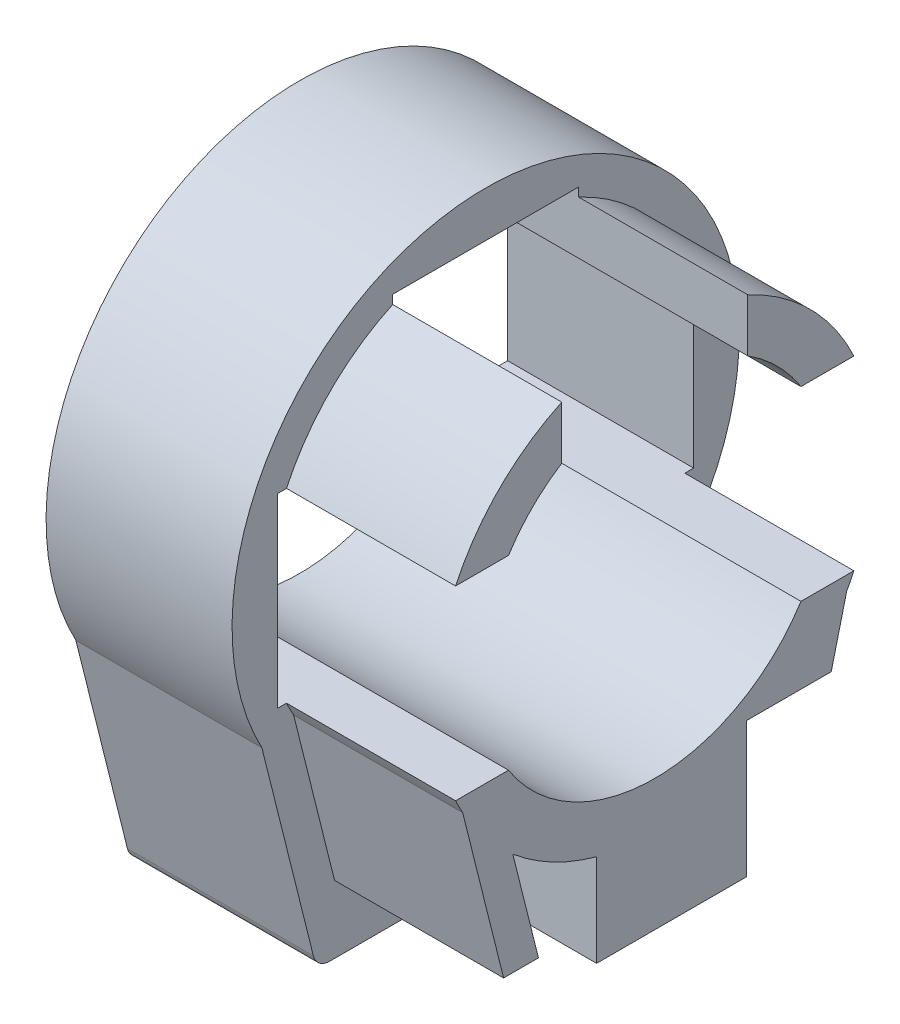
SolidWorks part; units mm, degrees
ref_plane "Alzado" through (0, 0, 0) normal (0, 0, 1) x (1, 0, 0)
ref_plane "Planta" through (0, 0, 0) normal (0, 1, 0) x (1, 0, 0)
ref_plane "Vista lateral" through (0, 0, 0) normal (1, 0, 0) x (0, 0, -1)
sketch "Croquis1" plane through (0, 0, 0) normal (1, 0, 0) x (0, 0, -1)
  line L0 (-15, 35) -> (-15, 30) construction
  line L1 (-5.7808, 0) -> (-24.2192, 0)
  line L5 (-15, 30) -> (-15, 10) construction
  line L6 (-25, 20) -> (-25, 0) construction
  line L7 (-5, 20) -> (-5, 0) construction
  line L8 (-28.2353, 12.9412) -> (-25.1894, 0.7575)
  line L9 (-1.7647, 12.9412) -> (-4.8106, 0.7575)
  circle A0 centre (-15, 20) radius 10
  arc A1 (-1.7647, 12.9412) -> (-28.2353, 12.9412) centre (-15, 20) ccw
  arc A2 (-24.2192, 0) -> (-25.1894, 0.7575) centre (-24.2192, 1) cw
  arc A3 (-5.7808, 0) -> (-4.8106, 0.7575) centre (-5.7808, 1) ccw
  dimension "D1" = 1
  dimension "D2" = 35
  dimension "D3" = 20
  dimension "D4" = 5
extrude "Saliente-Extruir1" add sketch "Croquis1" along normal blind 11
sketch "Croquis2" plane through (11, 0, 0) normal (1, 0, 0) x (0, 0, -1)
  line L9 (-23.4384, 2) -> (-6.5616, 2)
  line L10 (-6.5616, 2) -> (-3.6431, 13.6738)
  line L11 (-26.3569, 13.6738) -> (-23.4384, 2)
  line L12 (-23.4384, 2) -> (-6.5616, 2)
  line L13 (-6.5616, 2) -> (-3.6431, 13.6738)
  line L14 (-26.3569, 13.6738) -> (-23.4384, 2)
  circle A6 centre (-15, 20) radius 10 construction
  circle A7 centre (-15, 20) radius 10
  arc A9 (-3.6431, 13.6738) -> (-26.3569, 13.6738) centre (-15, 20) ccw
  arc A10 (-3.6431, 13.6738) -> (-26.3569, 13.6738) centre (-15, 20) ccw
  dimension "D1" = 2
extrude "Saliente-Extruir2" add sketch "Croquis2" along normal blind 10
sketch "Croquis3" plane through (21, 0, 0) normal (1, 0, 0) x (0, 0, -1)
  line L0 (-9.5616, 2) -> (-9.5616, 10)
  line L1 (-23.4384, 2) -> (-6.5616, 2) construction
  line L2 (-9.5616, 10) -> (-4.5616, 10)
  line L3 (-6.5616, 2) -> (-3.6431, 13.6738) construction
  line L4 (-9.5616, 2) -> (-6.5616, 2)
  line L5 (-6.5616, 2) -> (-4.5616, 10)
  line L6 (-21.7673, 2) -> (-21.7673, 4) construction
  line L7 (-23.4384, 2) -> (-18.4384, 2)
  line L8 (-23.4384, 2) -> (-23.9384, 4)
  line L9 (-21.7673, 4) -> (-21.8769, 4) construction
  line L10 (-24.4166, 14.1589) -> (-21.4982, 2.4851)
  line L11 (-23.1946, 9.2708) -> (-21.8769, 4)
  line L12 (-21.8769, 4) -> (-23.9384, 4)
  line L13 (-26.3569, 13.6738) -> (-23.4384, 2) construction
  line L14 (-18.4384, 2) -> (-18.4384, 6.9452)
  line L15 (-23.1946, 9.2708) -> (-23.3955, 10.0745)
  line L16 (-18.4384, 6.9452) -> (-18.4384, 7.463)
  circle A6 centre (-15, 20) radius 13
  arc A7 (-23.3955, 10.0745) -> (-18.4384, 7.463) centre (-15, 20) ccw
  dimension "D2" = 8
  dimension "D3" = 5
  dimension "D4" = 2
  dimension "D6" = 5
  dimension "D5" = 2
  dimension "D7" = 3
extrude "Cortar-Extruir3" cut sketch "Croquis3" against normal blind 10
sketch "Croquis8" plane through (0, 2, 0) normal (0, -1, 0) x (1, 0, 0)
  line L1 (11, 14) -> (13.2177, 14) construction
  line L2 (11, 18.4384) -> (11, 9.5616) construction
  line L4 (14.45, 14) -> (16, 14) construction
  line L5 (16, 14) -> (17.55, 14) construction
  line L7 (17.55, 14) -> (21, 14) construction
  line L8 (21, 18.4384) -> (21, 9.5616) construction
  circle A0 centre (16, 14) radius 1.55
  dimension "D2" = 3.1
extrude "Cortar-Extruir4" cut sketch "Croquis8" against normal blind 5
sketch "Croquis10" plane through (0, 0, 0) normal (-1, 0, 0) x (0, 0, 1)
  line L4 (15, 32.3) -> (20.5, 32.3)
  line L5 (2.7, 20) -> (5, 20)
  line L6 (2.7, 20) -> (2.7, 25.5)
  line L9 (2.7, 20) -> (2.7, 14.5)
  line L10 (15, 32.3) -> (9.5, 32.3)
  line L11 (2.7, 25.5) -> (6.3506, 25.5)
  line L12 (2.7, 14.5) -> (6.3506, 14.5)
  line L13 (20.5, 32.3) -> (20.5, 28.6494)
  line L14 (9.5, 32.3) -> (9.5, 28.6494)
  line L16 (27.3, 20) -> (27.3, 14.5)
  line L17 (27.3, 20) -> (27.3, 25.5)
  line L18 (27.3, 14.5) -> (23.6494, 14.5)
  line L19 (27.3, 25.5) -> (23.6494, 25.5)
  line L21 (15, 20) -> (15, 30.25) construction
  arc A1 (9.5, 28.6494) -> (6.3506, 25.5) centre (15, 20) ccw
  arc A2 (23.6494, 25.5) -> (20.5, 28.6494) centre (15, 20) ccw
  arc A3 (6.3506, 14.5) -> (23.6494, 14.5) centre (15, 20) ccw
  circle A4 centre (15, 20) radius 10 construction
  dimension "D1" = 20.5
  dimension "D2" = 2.3
  dimension "D3" = 5.5
  dimension "D4" = 5.5
  dimension "D5" = 3
extrude "Cortar-Extruir8" cut sketch "Croquis10" against normal up to next
sketch "Croquis12" plane through (21, 0, 0) normal (1, 0, 0) x (0, 0, -1)
  line L0 (-19.2083, 32.3) -> (-10.7917, 32.3) construction
  line L1 (-27.3, 15.7917) -> (-27.3, 24.2083) construction
  line L2 (-2.7, 24.2083) -> (-2.7, 15.7917) construction
  line L3 (-19.2083, 32.3) -> (-10.7917, 32.3)
  line L4 (-27.3, 15.7917) -> (-27.3, 24.2083)
  line L5 (-2.7, 24.2083) -> (-2.7, 15.7917)
  arc A0 (-10.7917, 32.3) -> (-19.2083, 32.3) centre (-15, 20) ccw construction
  arc A1 (-27.3, 24.2083) -> (-27.3, 15.7917) centre (-15, 20) ccw construction
  arc A2 (-2.7, 15.7917) -> (-2.7, 24.2083) centre (-15, 20) ccw construction
  arc A3 (-10.7917, 32.3) -> (-19.2083, 32.3) centre (-15, 20) ccw
  arc A4 (-27.3, 24.2083) -> (-27.3, 15.7917) centre (-15, 20) ccw
  arc A5 (-2.7, 15.7917) -> (-2.7, 24.2083) centre (-15, 20) ccw
extrude "Cortar-Extruir9" cut sketch "Croquis12" against normal blind 10
